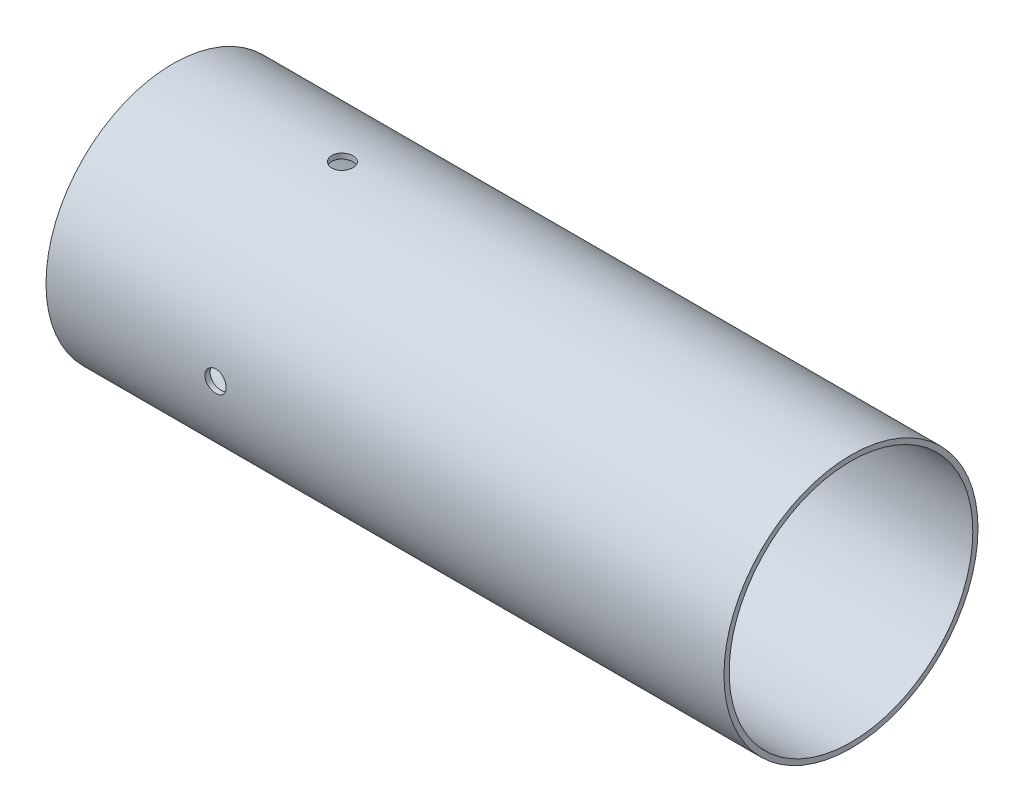
SolidWorks part; units mm, degrees
ref_plane "Front Plane" through (0, 0, 0) normal (1, 0, 0) x (0, 1, 0)
ref_plane "Top Plane" through (0, 0, 0) normal (0, 0, 1) x (0, 1, 0)
ref_plane "Right Plane" through (0, 0, 0) normal (0, 1, 0) x (-1, 0, 0)
sketch "Sketch1" plane through (0, 0, 0) normal (1, 0, 0) x (0, 1, 0)
  circle A0 centre (0, 0) radius 38.0746
  circle A1 centre (0, 0) radius 36.5125
  dimension "D1" = 76.1492
  dimension "D2" = 73.025
extrude "Boss-Extrude1" add sketch "Sketch1" along normal blind 203.2
sketch "Sketch3" plane through (0, 0, 0) normal (0, 1, 0) x (-1, 0, 0)
  line L0 (0, -38.0746) -> (0, 38.0746) construction
  line L1 (0, -38.0746) -> (0, 38.0746) construction
  line L2 (0, 0) -> (-50.8, 0) construction
  circle A0 centre (-50.8, 0) radius 3.175
  dimension "D2" = 6.35
  dimension "D1" = 50.8
extrude "Cut-Extrude1" cut sketch "Sketch3" along normal through all
pattern_circular "CirPattern1" count 4 over 360 about axis through (203.2, 0, 0) along (-1, 0, 0) of "Cut-Extrude1"
